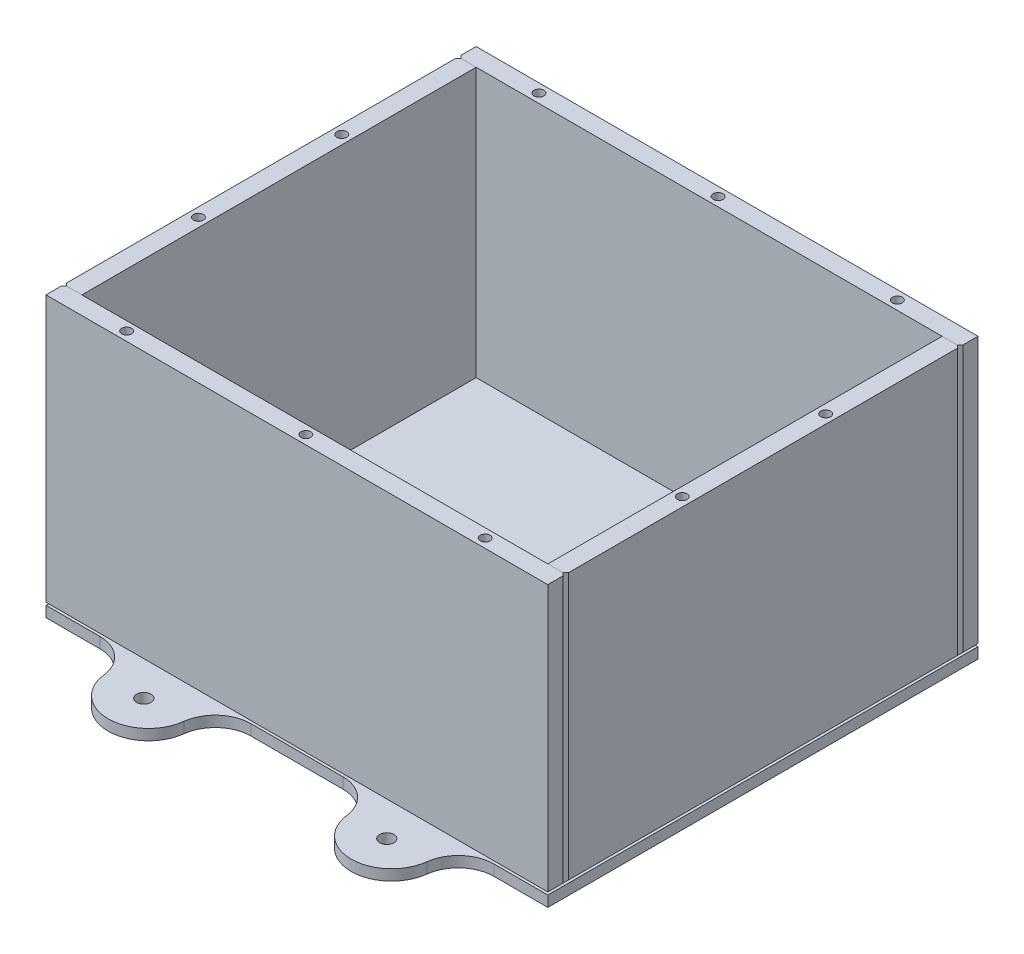
SolidWorks part; units mm, degrees
other "Elemento de detalle1"
other "Elemento de detalle2"
other "Elemento de detalle3"
other "Elemento de detalle4"
other "Elemento de detalle6"
other "Elemento de detalle7"
other "Elemento de detalle8"
other "Elemento de detalle9"
other "Elemento de detalle10"
other "Carpeta de soldadura"
other "Cordón de soldadura1"
other "Cordón de soldadura2"
other "Cordón de soldadura6"
other "Cordón de soldadura7"
other "Cordón de soldadura8"
other "Cordón de soldadura10"
other "Cordón de soldadura9"
material "7075-O (SS)"
ref_plane "Front" through (0, 0, 0) normal (0, 0, 1) x (1, 0, 0)
ref_plane "Top" through (0, 0, 0) normal (0, 1, 0) x (1, 0, 0)
ref_plane "Right" through (0, 0, 0) normal (1, 0, 0) x (0, 0, -1)
sketch "Croquis1" plane through (0, 0, 0) normal (0, 1, 0) x (1, 0, 0)
  line L0 (-25.5903, 120) -> (25.5903, 120)
  line L1 (-140, -120) -> (-110, -120)
  line L2 (-140, -120) -> (-140, 120)
  line L3 (-140, 120) -> (-110, 120)
  line L4 (140, -120) -> (140, 120)
  line L5 (-140, -120) -> (140, 120) construction
  line L6 (-140, 120) -> (140, -120) construction
  line L7 (0, -55) -> (0, 55) construction
  line L8 (-55, 0) -> (55, 0) construction
  line L9 (110, 120) -> (140, 120)
  line L10 (110, -120) -> (140, -120)
  line L11 (-25.5903, -120) -> (25.5903, -120)
  arc A0 (-45.4514, 137.6471) -> (-90.1389, 137.6471) centre (-67.7951, 135) ccw
  arc A1 (-110, 120) -> (-90.1389, 137.6471) centre (-110, 140) ccw
  arc A2 (-45.4514, 137.6471) -> (-25.5903, 120) centre (-25.5903, 140) ccw
  circle A3 centre (-67.7951, 137.6471) radius 4
  circle A4 centre (67.7951, 137.6471) radius 4
  arc A5 (45.4514, 137.6471) -> (25.5903, 120) centre (25.5903, 140) cw
  arc A6 (45.4514, 137.6471) -> (90.1389, 137.6471) centre (67.7951, 135) cw
  arc A7 (110, 120) -> (90.1389, 137.6471) centre (110, 140) cw
  circle A8 centre (67.7951, -137.6471) radius 4
  arc A9 (110, -120) -> (90.1389, -137.6471) centre (110, -140) ccw
  arc A10 (45.4514, -137.6471) -> (90.1389, -137.6471) centre (67.7951, -135) ccw
  arc A11 (45.4514, -137.6471) -> (25.5903, -120) centre (25.5903, -140) ccw
  circle A12 centre (-67.7951, -137.6471) radius 4
  arc A13 (-45.4514, -137.6471) -> (-90.1389, -137.6471) centre (-67.7951, -135) cw
  arc A14 (-110, -120) -> (-90.1389, -137.6471) centre (-110, -140) cw
  arc A15 (-45.4514, -137.6471) -> (-25.5903, -120) centre (-25.5903, -140) cw
  point P0 (0, 0)
  dimension "D3" = 40
  dimension "D4" = 45
  dimension "D7" = 8
  dimension "D1" = 240
  dimension "D2" = 280
  dimension "D5" = 30
  dimension "D6" = 15
extrude "Saliente-Extruir1" add sketch "Croquis1" along normal mid plane 6
sketch "Croquis2" plane through (0, 3, 0) normal (0, 1, 0) x (1, 0, 0)
  line L0 (140, -120) -> (140, 120) construction
  line L5 (-140, 120) -> (140, 120)
  line L6 (-140, 120) -> (-140, 110)
  line L11 (-140, 110) -> (140, 110)
  line L12 (140, 120) -> (140, 110)
  line L14 (-140, -120) -> (140, -120)
  line L15 (-140, -120) -> (-140, -110)
  line L16 (-140, -110) -> (140, -110)
  line L17 (140, -120) -> (140, -110)
  dimension "D1" = 10
extrude "Saliente-Extruir2" add sketch "Croquis2" along normal blind 150 separate body
sketch "Croquis3" plane through (0, 3, 0) normal (0, 1, 0) x (1, 0, 0)
  line L0 (140, -110) -> (-140, -110) construction
  line L1 (-140, 110) -> (-130, 110)
  line L2 (-140, 110) -> (-140, -110)
  line L3 (-140, -110) -> (-130, -110)
  line L4 (-130, 110) -> (-130, -110)
  line L6 (140, 110) -> (130, 110)
  line L7 (140, 110) -> (140, -110)
  line L8 (140, -110) -> (130, -110)
  line L9 (130, 110) -> (130, -110)
  dimension "D1" = 10
extrude "Saliente-Extruir3" add sketch "Croquis3" along normal blind 150 separate body
chamfer "Chaflán1" distance 1.5 angle 45 3 edges at (-140, 78, 110) (-140, 3, 0) (-140, 78, -110)
chamfer "Chaflán2" distance 1.5 angle 45 5 edges at (140, 78, -110) (140, 3, -115) (0, 3, -120) (-140, 3, -115) (-140, 78, -110)
chamfer "Chaflán3" distance 1.5 angle 45 5 edges at (140, 78, 110) (140, 3, 115) (0, 3, 120) (-140, 3, 115) (-140, 78, 110)
chamfer "Chaflán4" distance 1.5 angle 45 3 edges at (140, 78, -110) (140, 3, 0) (140, 78, 110)
hole_wizard "Taladro de margen para M51" positions "Croquis4" profile "Croquis5" hole size "M5" standard "Ansi Metric"
sketch "Croquis4" plane through (0, 153, 0) normal (0, 1, 0) x (1, 0, 0)
  line L0 (-135, 40) -> (-135, -40) construction
  line L3 (-100, 115) -> (100, 115) construction
  line L6 (135, 40) -> (135, -40) construction
  line L9 (100, -115) -> (-100, -115) construction
  line L12 (0, -85.8) -> (0, 85.8) construction
  line L13 (-85.8, 0) -> (85.8, 0) construction
  line L14 (-135, 0) -> (135, 0) construction
  line L17 (0, 115) -> (0, -115) construction
  point P0 (-135, 40)
  point P1 (-135, -40)
  point P5 (-100, 115)
  point P6 (100, 115)
  point P9 (135, 40)
  point P10 (135, -40)
  point P13 (100, -115)
  point P14 (-100, -115)
  point P18 (0, 115)
  point P21 (0, -115)
  point P22 (-135, 0)
  point P25 (135, 0)
  point P31 (0, 0)
  point P33 (0, 115)
  point P34 (0, -115)
  point P39 (0, 0)
  dimension "D1" = 230
  dimension "D2" = 270
  dimension "D3" = 200
  dimension "D4" = 80
sketch "Croquis5" plane through (-135, 153, -40) normal (1, 0, 0) x (0, 0, 1)
  line L0 (0, 0) -> (0, 21.6524)
  line L1 (0, 21.6524) -> (2.75, 20)
  line L2 (2.75, 20) -> (2.75, 0)
  line L5 (2.75, 0) -> (0, 0)
  line L10 (0, 21.6524) -> (-2.75, 20) construction
  line L11 (0, -6.35) -> (0, 107.95) construction
  dimension "Diámetro de taladro" = 5.5
  dimension "Profundidad de taladro" = 20
  dimension "Ángulo de perforador" = 118
